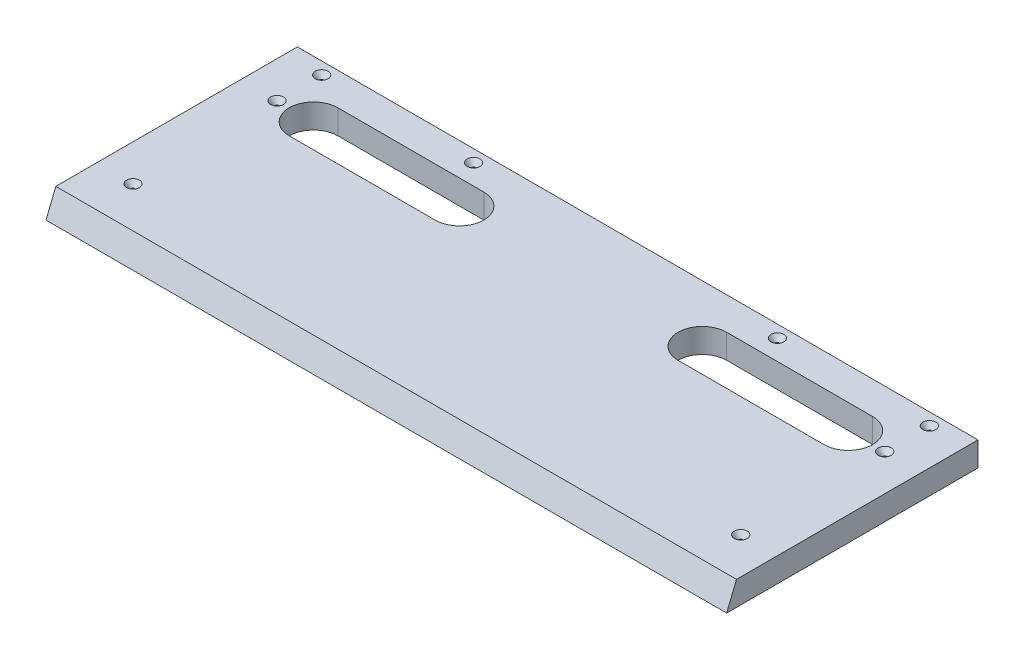
SolidWorks part; units mm, degrees
material "Beech"
ref_plane "Front Plane" through (0, 0, 0) normal (0, 0, 1) x (1, 0, 0)
ref_plane "Top Plane" through (0, 0, 0) normal (0, 1, 0) x (1, 0, 0)
ref_plane "Right Plane" through (0, 0, 0) normal (1, 0, 0) x (0, 0, -1)
sketch "Sketch1" plane through (0, 3140.71, 0) normal (0, 1, 0) x (1, 0, 0)
  line L1 (266.573, 7002.78) -> (-266.573, 7002.78)
  line L2 (266.573, 7002.78) -> (266.573, 6805.9166)
  line L3 (266.573, 6805.9166) -> (-266.573, 6805.9166)
  line L4 (-266.573, 7002.78) -> (-266.573, 6805.9166)
extrude "Boss-Extrude1" add sketch "Sketch1" along normal blind 19.05
sketch "Sketch2" plane through (266.573, 0, 0) normal (1, 0, 0) x (0, 0, -1)
  line L0 (6805.9166, 3140.71) -> (6813.6133, 3159.76)
  line L1 (6805.9166, 3159.76) -> (7002.78, 3159.76) construction
  line L2 (6813.6133, 3159.76) -> (6805.9166, 3159.76)
  line L3 (6805.9166, 3159.76) -> (6805.9166, 3140.71)
  line L4 (6621.1958, 2683.51) -> (6805.9166, 3140.71) construction
extrude "Cut-Extrude1" cut sketch "Sketch2" against normal through all
sketch "Sketch3" plane through (0, 3159.76, 0) normal (0, 1, 0) x (1, 0, 0)
  line L0 (209.423, 6958.33) -> (95.123, 6958.33) construction
  line L1 (209.423, 6939.28) -> (95.123, 6939.28)
  line L2 (209.423, 6977.38) -> (95.123, 6977.38)
  line L4 (266.573, 7002.78) -> (-266.573, 7002.78) construction
  line L5 (266.573, 6813.6133) -> (266.573, 7002.78) construction
  line L6 (0, 7002.78) -> (0, 6813.6133) construction
  line L7 (-266.573, 6813.6133) -> (266.573, 6813.6133) construction
  line L8 (-209.423, 6958.33) -> (-95.123, 6958.33) construction
  line L9 (-209.423, 6939.28) -> (-95.123, 6939.28)
  line L10 (-209.423, 6977.38) -> (-95.123, 6977.38)
  arc A0 (209.423, 6939.28) -> (209.423, 6977.38) centre (209.423, 6958.33) ccw
  arc A1 (95.123, 6977.38) -> (95.123, 6939.28) centre (95.123, 6958.33) ccw
  arc A2 (-209.423, 6939.28) -> (-209.423, 6977.38) centre (-209.423, 6958.33) cw
  arc A3 (-95.123, 6977.38) -> (-95.123, 6939.28) centre (-95.123, 6958.33) cw
  point P2 (152.273, 6958.33)
  point P17 (-152.273, 6958.33)
  dimension "D1" = 38.1
  dimension "D2" = 25.4
  dimension "D3" = 114.3
  dimension "D4" = 114.3
extrude "Cut-Extrude2" cut sketch "Sketch3" against normal through all
hole_wizard "Hole1" positions "Sketch4" profile "Sketch5" legacy
sketch "Sketch4" plane through (0, 3159.76, 0) normal (0, 1, 0) x (1, 0, 0)
  line L0 (237.998, 6813.6133) -> (237.998, 7002.78) construction
  line L5 (0, 6813.6133) -> (0, 7002.78) construction
  line L7 (266.573, 6993.255) -> (-266.573, 6993.255) construction
  line L17 (237.998, 6845.5127) -> (237.998, 6958.33)
  line L18 (237.998, 6993.255) -> (0, 6993.255)
  point P30 (237.998, 6993.255)
  point P32 (237.998, 6958.33)
  point P34 (237.998, 6845.5127)
  point P50 (-237.998, 6993.255)
  point P51 (-237.998, 6958.33)
  point P52 (-237.998, 6845.5127)
  point P60 (118.999, 6993.255)
  point P64 (-118.999, 6993.255)
sketch "Sketch5" plane through (-118.999, 3159.76, -6993.255) normal (1, 0, 0) x (0, 0, 1)
  line L0 (0, 0) -> (0, 39.0539)
  line L1 (0, 39.0539) -> (1.5875, 38.1)
  line L2 (1.5875, 38.1) -> (1.5875, 4.0177)
  line L3 (1.5875, 4.0177) -> (5.08, 0)
  line L4 (5.08, 0) -> (0, 0)
  line L5 (0, -14.3089) -> (0, 102.4216) construction
  line L6 (0, 39.0539) -> (-1.5875, 38.1) construction
  line L7 (-1.5875, 4.0177) -> (-5.08, 0) construction
  dimension "Diameter" = 3.175
  dimension "Depth" = 38.1
  dimension "C-Sink Diameter" = 10.16
  dimension "C-Sink Angle" = 82
  dimension "Drill Angle" = 118
